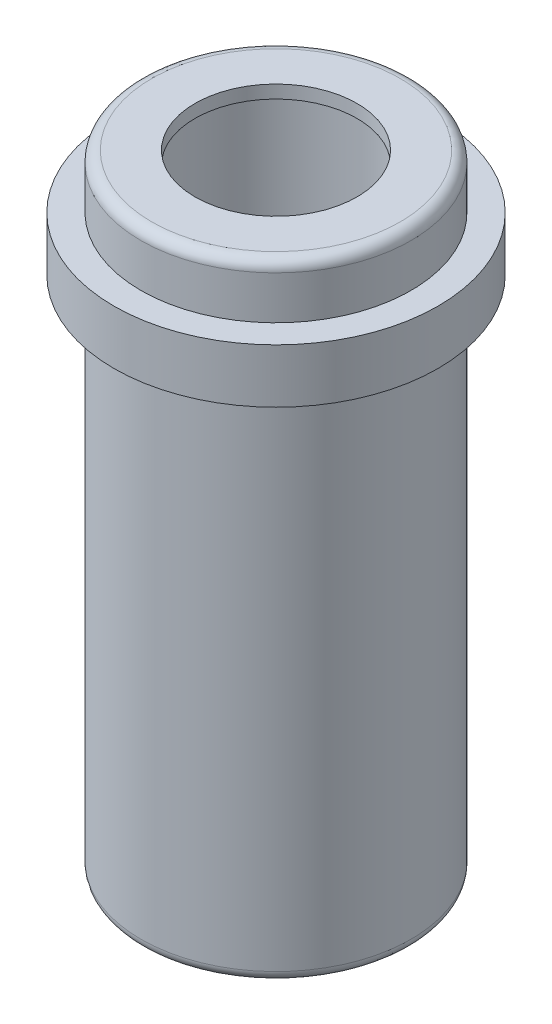
SolidWorks part; units mm, degrees
ref_plane "前视基准面" through (0, 0, 0) normal (0, 0, 1) x (1, 0, 0)
ref_plane "上视基准面" through (0, 0, 0) normal (0, 1, 0) x (1, 0, 0)
ref_plane "右视基准面" through (0, 0, 0) normal (1, 0, 0) x (0, 0, -1)
sketch "草图1" plane through (0, 0, 0) normal (0, 0, 1) x (1, 0, 0)
  line L0 (0, 8.2388) -> (0, -6.3059) construction
  line L1 (0, -4.8) -> (-1.25, -4.8)
  line L2 (-1.25, -4.8) -> (-1.25, 0)
  line L3 (-1.25, 0) -> (-1.5, 0)
  line L4 (-1.5, 0) -> (-1.5, 0.5)
  line L5 (-1.5, 0.5) -> (-1.25, 0.5)
  line L6 (-1.25, 0.5) -> (-1.25, 1)
  line L7 (-1.25, 1) -> (-0.75, 1)
  line L8 (-0.75, 1) -> (-0.75, 0.8797)
  line L9 (-0.75, 0.8797) -> (-0.9032, 0.8797)
  line L10 (-0.9032, 0.8797) -> (-0.9032, -3.6)
  line L11 (-0.9032, -3.6) -> (0, -4.2041)
  line L12 (5.0295, 0) -> (-9.301, 0) construction
  line L13 (0, -4.8) -> (0, -4.2041)
  point P15 (-0.625, -4.8)
  point P18 (0, -2.7866)
  point P19 (-3.0949, -1.9215)
  point P20 (0, -4.3852)
  point P21 (0, -4.2041)
  point P22 (-0.75, 0.9399)
  point P23 (-1.5, 0.25)
  dimension "D1" = 4.8
  dimension "D2" = 0.5
  dimension "D3" = 4.6
  dimension "D4" = 0.5
  dimension "D5" = 1.25
  dimension "D6" = 1.5
  dimension "D7" = 0.75
revolve "旋转1" add sketch "草图1" angle 360 about L0
fillet "圆角1" radius 0.1 2 edges at (0, 1, 1.25) (0, -4.8, 1.25)
